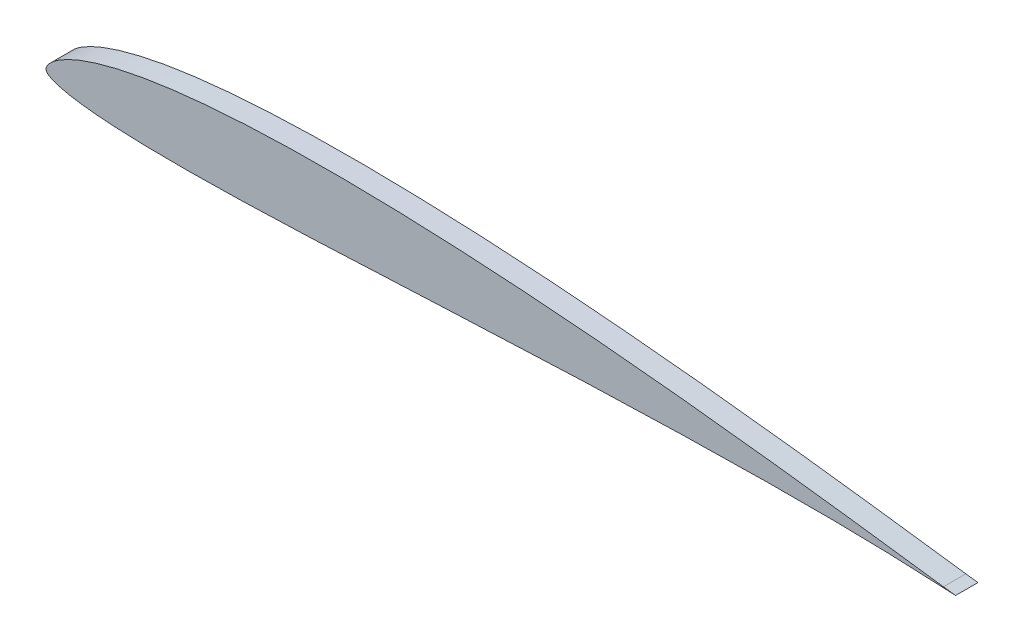
SolidWorks part; units mm, degrees
ref_plane "Front Plane"
ref_plane "Top Plane" through (0, 0, 0) normal (0, 1, 0) x (1, 0, 0)
ref_plane "Right Plane" through (0, 0, 0) normal (1, 0, 0) x (0, 0, -1)
curve "Curve1"
  spline degree 3 poles (25.4, 0.0072, 0) (25.3496, 0.0134, 0) (25.1976, 0.032, 0) (24.931, 0.0678, 0) (24.5974, 0.1122, 0) (24.2481, 0.1596, 0) (23.8959, 0.2071, 0) (23.5433, 0.2543, 0) (23.1906, 0.3008, 0) (22.8379, 0.3469, 0) (22.4851, 0.3923, 0) (22.1324, 0.4371, 0) (21.7796, 0.4814, 0) (21.4269, 0.5252, 0) (21.0741, 0.5684, 0) (20.7213, 0.6111, 0) (20.3686, 0.6531, 0) (20.0157, 0.6946, 0) (19.6629, 0.7353, 0) (19.3099, 0.7754, 0) (18.9569, 0.8148, 0) (18.6039, 0.8534, 0) (18.2507, 0.8914, 0) (17.8975, 0.9285, 0) (17.5443, 0.9649, 0) (17.1911, 1.0004, 0) (16.8378, 1.035, 0) (16.4846, 1.0687, 0) (16.1313, 1.1015, 0) (15.7779, 1.1332, 0) (15.4246, 1.1639, 0) (15.0713, 1.1936, 0) (14.718, 1.2223, 0) (14.3647, 1.2498, 0) (14.0115, 1.2762, 0) (13.6582, 1.3015, 0) (13.3049, 1.3256, 0) (12.9518, 1.3485, 0) (12.5986, 1.3701, 0) (12.2455, 1.3905, 0) (11.8924, 1.4095, 0) (11.5394, 1.4272, 0) (11.1865, 1.4435, 0) (10.8337, 1.4583, 0) (10.481, 1.4717, 0) (10.1284, 1.4834, 0) (9.7759, 1.4936, 0) (9.4236, 1.502, 0) (9.0714, 1.5087, 0) (8.7195, 1.5136, 0) (8.3678, 1.5165, 0) (8.0163, 1.5173, 0) (7.6651, 1.5159, 0) (7.3143, 1.5124, 0) (6.9638, 1.5064, 0) (6.6137, 1.4978, 0) (6.2641, 1.4865, 0) (5.9151, 1.4723, 0) (5.5667, 1.4549, 0) (5.2191, 1.4342, 0) (4.8724, 1.41, 0) (4.5268, 1.3818, 0) (4.1824, 1.3496, 0) (3.8397, 1.3127, 0) (3.4989, 1.271, 0) (3.1604, 1.2238, 0) (2.8247, 1.1707, 0) (2.4925, 1.111, 0) (2.1648, 1.044, 0) (1.8428, 0.9688, 0) (1.5284, 0.8845, 0) (1.2246, 0.7903, 0) (0.937, 0.686, 0) (0.6762, 0.5736, 0) (0.4574, 0.4593, 0) (0.2915, 0.3529, 0) (0.1774, 0.2622, 0) (0.1028, 0.1892, 0) (0.0545, 0.1298, 0) (0.0231, 0.0799, 0) (0.0044, 0.0362, 0) (-0.0025, -0.005, 0) (0.0063, -0.0456, 0) (0.0328, -0.0835, 0) (0.0761, -0.1189, 0) (0.1391, -0.1556, 0) (0.232, -0.1961, 0) (0.3706, -0.242, 0) (0.5672, -0.2906, 0) (0.8203, -0.3374, 0) (1.1146, -0.3772, 0) (1.4317, -0.4098, 0) (1.7604, -0.435, 0) (2.0955, -0.4541, 0) (2.4346, -0.4681, 0) (2.7765, -0.4779, 0) (3.1205, -0.4843, 0) (3.466, -0.4876, 0) (3.8127, -0.4882, 0) (4.1605, -0.4866, 0) (4.509, -0.4829, 0) (4.8582, -0.4773, 0) (5.2079, -0.4701, 0) (5.5581, -0.4614, 0) (5.9087, -0.4514, 0) (6.2597, -0.4403, 0) (6.611, -0.4281, 0) (6.9627, -0.415, 0) (7.3147, -0.4012, 0) (7.6671, -0.3868, 0) (8.0197, -0.3717, 0) (8.3727, -0.3562, 0) (8.726, -0.3403, 0) (9.0797, -0.324, 0) (9.4337, -0.3075, 0) (9.788, -0.2908, 0) (10.1425, -0.274, 0) (10.497, -0.2571, 0) (10.8513, -0.2402, 0) (11.2054, -0.2234, 0) (11.5592, -0.2066, 0) (11.9127, -0.1901, 0) (12.2661, -0.1738, 0) (12.6192, -0.1577, 0) (12.9722, -0.1419, 0) (13.3251, -0.1264, 0) (13.6779, -0.1113, 0) (14.0305, -0.0965, 0) (14.383, -0.0821, 0) (14.7355, -0.0683, 0) (15.0879, -0.0548, 0) (15.4401, -0.0418, 0) (15.7922, -0.0294, 0) (16.1442, -0.0175, 0) (16.4961, -0.0062, 0) (16.8479, 0.0046, 0) (17.1997, 0.0147, 0) (17.5515, 0.0243, 0) (17.9033, 0.0332, 0) (18.2551, 0.0415, 0) (18.6069, 0.0492, 0) (18.9589, 0.0563, 0) (19.3108, 0.0627, 0) (19.6628, 0.0683, 0) (20.0149, 0.0732, 0) (20.3672, 0.0771, 0) (20.7195, 0.0802, 0) (21.0719, 0.0821, 0) (21.4244, 0.083, 0) (21.7769, 0.0825, 0) (22.1295, 0.0808, 0) (22.4822, 0.0776, 0) (22.8349, 0.0728, 0) (23.1876, 0.0662, 0) (23.5404, 0.058, 0) (23.8931, 0.0477, 0) (24.2457, 0.0356, 0) (24.5959, 0.0216, 0) (24.9302, 0.0067, 0) (25.1975, -0.0068, 0) (25.3496, -0.0147, 0) (25.4, -0.0173, 0) knots 0 0 0 0 0.002964 0.008954 0.015716 0.022625 0.029553 0.036482 0.043411 0.05034 0.057267 0.064194 0.071118 0.078042 0.084963 0.091884 0.098805 0.105723 0.112642 0.11956 0.126478 0.133396 0.140315 0.147231 0.154146 0.161062 0.167976 0.174887 0.181798 0.188708 0.195614 0.20252 0.209425 0.216326 0.223226 0.230125 0.237022 0.243914 0.250805 0.257696 0.264583 0.271465 0.278348 0.285225 0.292099 0.298971 0.30584 0.312703 0.319563 0.32642 0.333271 0.340115 0.346957 0.353791 0.360616 0.367439 0.374252 0.381055 0.387851 0.394633 0.401403 0.408159 0.414893 0.421609 0.428299 0.434956 0.441581 0.448155 0.454677 0.46112 0.467474 0.473691 0.479702 0.485343 0.490272 0.494111 0.496842 0.498772 0.500199 0.501308 0.502204 0.502963 0.503709 0.504566 0.50561 0.50696 0.508816 0.511519 0.515478 0.520644 0.526552 0.532824 0.539269 0.545815 0.552433 0.559099 0.565803 0.572534 0.57929 0.586062 0.592853 0.599655 0.606468 0.613292 0.620125 0.626963 0.633811 0.640665 0.647526 0.654395 0.66127 0.668152 0.675041 0.681937 0.688839 0.695747 0.70266 0.709576 0.716486 0.723389 0.730287 0.737182 0.744071 0.750955 0.757837 0.764717 0.771594 0.778469 0.785341 0.792212 0.799079 0.805944 0.812807 0.819667 0.826524 0.83338 0.840234 0.847088 0.853942 0.860796 0.867651 0.874506 0.881363 0.888221 0.895078 0.901939 0.908802 0.915666 0.92253 0.929398 0.936265 0.943134 0.950005 0.956876 0.963749 0.970622 0.977497 0.98436 0.991101 0.997053 1 1 1 1
sketch "Sketch2" plane through (0, 0, 0) normal (0, 0, 1) x (1, 0, 0)
  line L0 (203.2, -0.1006) -> (203.2, -0.3165) construction
  line L1 (203.2, -0.1006) -> (205.9502, -0.438)
  line L2 (0, 0) -> (203.2, -0.3165) construction
  line L3 (205.9502, -0.438) -> (203.2, -0.2963)
  spline S1 degree 3 poles (203.2, -0.1006) (202.7972, -0.0512) (201.5805, 0.098) (199.448, 0.3845) (196.7798, 0.7397) (193.9851, 1.119) (191.1674, 1.4985) (188.3468, 1.8762) (185.5254, 2.2483) (182.7037, 2.6167) (179.8816, 2.9799) (177.0596, 3.3388) (174.2375, 3.6928) (170.4755, 4.16) (166.7127, 4.6181) (162.9496, 5.0667) (160.1271, 5.3984) (157.3042, 5.7241) (154.4808, 6.0452) (151.6569, 6.3601) (148.8323, 6.6691) (146.0074, 6.9726) (143.182, 7.2697) (140.3564, 7.5605) (137.5304, 7.8445) (134.7045, 8.1218) (131.8784, 8.3916) (129.0521, 8.6534) (126.2257, 8.9075) (123.3993, 9.1531) (120.5729, 9.3908) (116.8049, 9.696) (113.0366, 9.9841) (109.268, 10.2536) (105.5009, 10.5109) (101.7336, 10.748) (97.9666, 10.9655) (95.1421, 11.1176) (92.3183, 11.2592) (89.4952, 11.3894) (86.6728, 11.5083) (82.9115, 11.6502) (78.2126, 11.7969) (73.5147, 11.8981) (69.7595, 11.9503) (66.9459, 11.9732) (64.1341, 11.9803) (61.3248, 11.9691) (58.5181, 11.941) (55.7144, 11.8926) (52.9139, 11.8241) (49.1872, 11.7034) (45.4677, 11.5361) (41.757, 11.3153) (38.9834, 11.1213) (36.2188, 10.8962) (33.4643, 10.6384) (30.7227, 10.343) (27.9961, 10.0096) (25.2878, 9.6322) (22.6025, 9.2074) (19.9448, 8.73) (17.3237, 8.1936) (14.7478, 7.592) (12.2328, 6.9181) (9.8022, 6.1644) (7.5013, 5.3301) (5.4152, 4.4306) (3.6646, 3.5165) (2.3374, 2.6648) (1.4251, 1.9392) (0.828, 1.3554) (0.4413, 0.8801) (0.1908, 0.4809) (0.0405, 0.1314) (-0.014, -0.1981) (0.0558, -0.5226) (0.2679, -0.8257) (0.6148, -1.1092) (1.1188, -1.4029) (1.8618, -1.7266) (2.9701, -2.0938) (4.5434, -2.4832) (6.5683, -2.8571) (8.9222, -3.176) (11.4591, -3.4362) (14.0888, -3.6382) (16.7693, -3.7905) (19.482, -3.9027) (22.2173, -3.9811) (24.9689, -4.0322) (27.733, -4.0585) (30.5068, -4.0639) (33.2886, -4.0511) (36.0766, -4.021) (38.87, -3.9762) (41.6678, -3.9187) (44.4693, -3.8494) (47.2742, -3.7696) (50.082, -3.6803) (52.8926, -3.5832) (55.7058, -3.4782) (58.5217, -3.3675) (61.3404, -3.2521) (64.1617, -3.1318) (66.9856, -3.0079) (69.8121, -2.8802) (72.6414, -2.7504) (75.4732, -2.6181) (79.253, -2.4401) (83.0338, -2.26) (86.8139, -2.0796) (89.6462, -1.9452) (92.4765, -1.811) (95.305, -1.6788) (98.1316, -1.5482) (100.9565, -1.42) (103.7803, -1.293) (106.6033, -1.1694) (109.4254, -1.0485) (112.2464, -0.9304) (115.0668, -0.8151) (117.8864, -0.7043) (120.7051, -0.5963) (123.5228, -0.4928) (126.3398, -0.3931) (130.0938, -0.2664) (133.847, -0.1483) (137.5996, -0.0404) (140.4137, 0.0362) (143.2278, 0.1074) (146.9805, 0.1964) (150.7339, 0.275) (154.488, 0.3438) (157.304, 0.3881) (160.1208, 0.4273) (162.9384, 0.459) (165.7569, 0.4832) (168.5761, 0.4985) (171.3957, 0.5057) (174.216, 0.5019) (177.0367, 0.4882) (179.8579, 0.4628) (182.6795, 0.4244) (185.5014, 0.3715) (188.3233, 0.3056) (191.1454, 0.2236) (193.9656, 0.1263) (196.7671, 0.0146) (199.4417, -0.1043) (201.5802, -0.2129) (202.797, -0.2755) (203.2, -0.2963) knots 0 0 0 0 0.002964 0.008954 0.015716 0.022625 0.029553 0.036482 0.043411 0.05034 0.057267 0.064194 0.071118 0.078042 0.091884 0.098805 0.105723 0.112642 0.11956 0.126478 0.133396 0.140315 0.147231 0.154146 0.161062 0.167976 0.174887 0.181798 0.188708 0.195614 0.20252 0.209425 0.223226 0.230125 0.237022 0.250805 0.257696 0.264583 0.271465 0.278348 0.285225 0.292099 0.30584 0.319563 0.32642 0.333271 0.340115 0.346957 0.353791 0.360616 0.367439 0.374252 0.387851 0.394633 0.401403 0.408159 0.414893 0.421609 0.428299 0.434956 0.441581 0.448155 0.454677 0.46112 0.467474 0.473691 0.479702 0.485343 0.490272 0.494111 0.496842 0.498772 0.500199 0.501308 0.502204 0.502963 0.503709 0.504566 0.50561 0.50696 0.508816 0.511519 0.515478 0.520644 0.526552 0.532824 0.539269 0.545815 0.552433 0.559099 0.565803 0.572534 0.57929 0.586062 0.592853 0.599655 0.606468 0.613292 0.620125 0.626963 0.633811 0.640665 0.647526 0.654395 0.66127 0.668152 0.675041 0.681937 0.688839 0.695747 0.709576 0.716486 0.723389 0.730287 0.737182 0.744071 0.750955 0.757837 0.764717 0.771594 0.778469 0.785341 0.792212 0.799079 0.805944 0.812807 0.819667 0.83338 0.840234 0.847088 0.853942 0.860796 0.874506 0.881363 0.888221 0.895078 0.901939 0.908802 0.915666 0.92253 0.929398 0.936265 0.943134 0.950005 0.956876 0.963749 0.970622 0.977497 0.98436 0.991101 0.997053 1 1 1 1
  point P0 (204.4238, 0.04)
  dimension "D1" = 203.2
extrude "Boss-Extrude2" add sketch "Sketch2" along normal blind 5.08 contours S1 L3 L1
